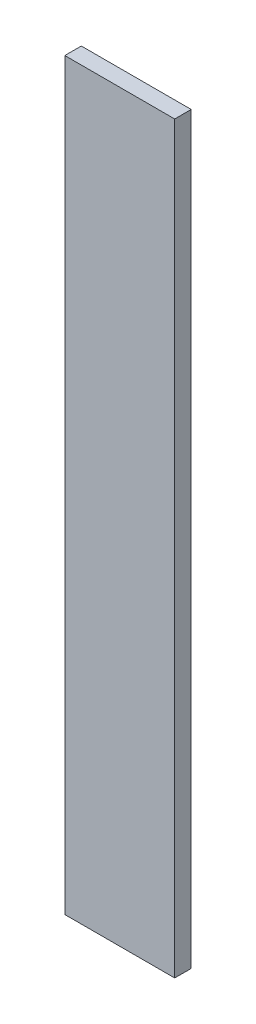
SolidWorks part; units mm, degrees
material "Простая углеродистая сталь"
ref_plane "Спереди" through (0, 0, 0) normal (0, 0, 1) x (1, 0, 0)
ref_plane "Сверху" through (0, 0, 0) normal (0, 1, 0) x (1, 0, 0)
ref_plane "Справа" through (0, 0, 0) normal (1, 0, 0) x (0, 0, -1)
sketch "Эскиз1" plane through (0, 0, 0) normal (0, 0, 1) x (1, 0, 0)
  line L1 (0, 0) -> (1000, 0)
  line L2 (0, 0) -> (0, -6770)
  line L3 (0, -6770) -> (1000, -6770)
  line L4 (1000, 0) -> (1000, -6770)
  line L5 (500, -6770) -> (500, 0) construction
  line L6 (0, -3385) -> (1000, -3385) construction
  point P244 (500, -3385)
  dimension "D1" = 6770
  dimension "D2" = 1000
extrude "Бобышка-Вытянуть1" add sketch "Эскиз1" along normal blind 150
